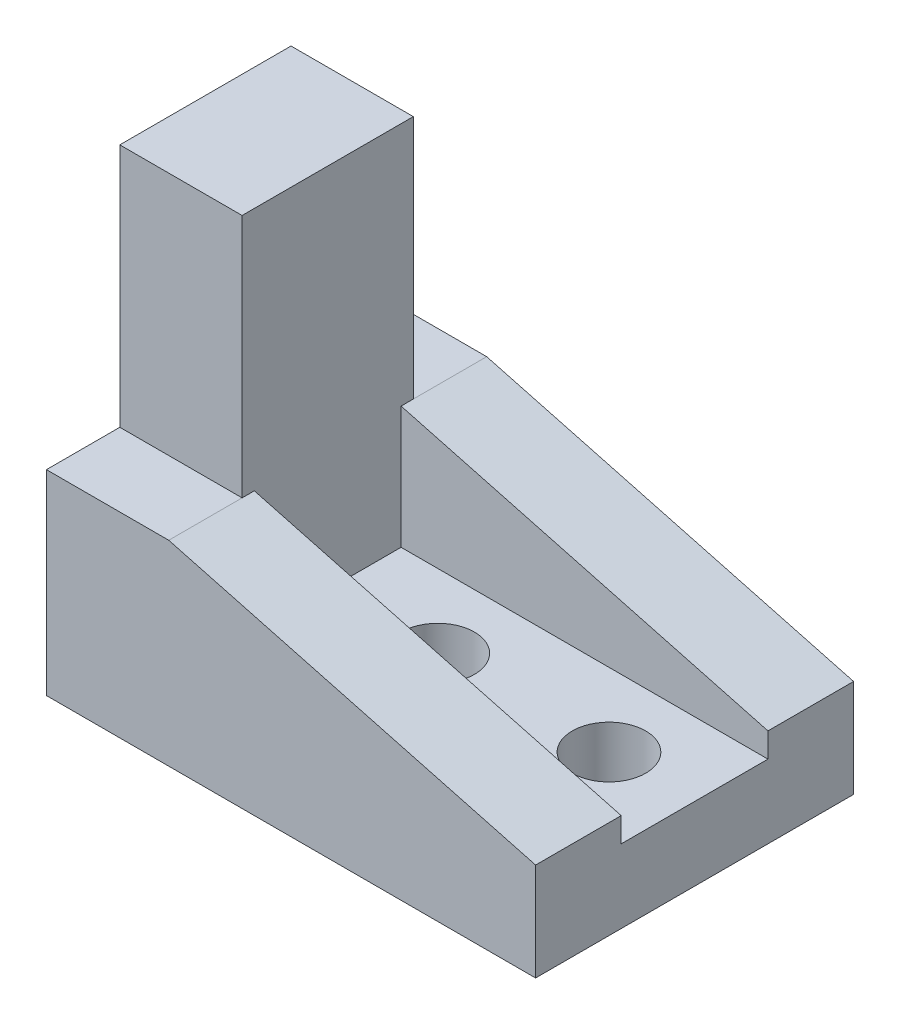
SolidWorks part; units mm, degrees
ref_plane "前视基准面" through (0, 0, 0) normal (0, 0, 1) x (1, 0, 0)
ref_plane "上视基准面" through (0, 0, 0) normal (0, 1, 0) x (1, 0, 0)
ref_plane "右视基准面" through (0, 0, 0) normal (1, 0, 0) x (0, 0, -1)
sketch "草图1" plane through (0, 0, 0) normal (0, 0, 1) x (1, 0, 0)
  line L0 (0, 0) -> (20, 0)
  line L1 (20, 0) -> (20, 4)
  line L2 (0, 0) -> (0, 18)
  line L3 (0, 18) -> (5, 18)
  line L4 (5, 18) -> (5, 8)
  line L5 (5, 8) -> (20, 4)
extrude "凸台-拉伸1" add sketch "草图1" along normal blind 13
sketch "草图2" plane through (0, 0, 0) normal (-1, 0, 0) x (0, 0, 1)
  line L0 (0, 0) -> (0, 8) construction
  line L1 (0, 18) -> (0, 0) construction
  line L2 (0, 8) -> (3, 8)
  line L3 (3, 8) -> (3, 18)
  line L4 (13, 18) -> (0, 18) construction
  line L5 (3, 18) -> (0, 18)
  line L6 (0, 18) -> (0, 8)
  line L7 (6.5, 18) -> (6.5, 0) construction
  line L8 (13, 0) -> (0, 0) construction
  line L9 (13, 18) -> (13, 8)
  line L10 (10, 18) -> (13, 18)
  line L11 (10, 8) -> (10, 18)
  line L12 (13, 8) -> (10, 8)
extrude "切除-拉伸1" cut sketch "草图2" against normal through all
ref_plane "基准面1" through (0, 8, 0) normal (0, -1, 0) x (-1, 0, 0)
sketch "草图3" plane through (0, 8, 0) normal (0, -1, 0) x (-1, 0, 0)
  line L4 (-5, -6.5) -> (-5, -9.5)
  line L5 (-5, -10) -> (-5, -3) construction
  line L6 (-5, -9.5) -> (-20, -9.5)
  line L7 (-20, -9.5) -> (-20, -3.5)
  line L8 (-20, -3.5) -> (-5, -3.5)
  line L9 (-5, -3.5) -> (-5, -6.5)
extrude "切除-拉伸2" cut sketch "草图3" along normal blind 5
sketch "草图4" plane through (0, 3, 0) normal (0, 1, 0) x (1, 0, 0)
  line L0 (20, -6.5) -> (16.5, -6.5) construction
  line L2 (20, -3.5) -> (20, -9.5) construction
  line L3 (20, -6.5) -> (9.5, -6.5) construction
  circle A0 centre (16.5, -6.5) radius 1.5
  circle A1 centre (9.5, -6.5) radius 1.5
extrude "切除-拉伸3" cut sketch "草图4" against normal through all
